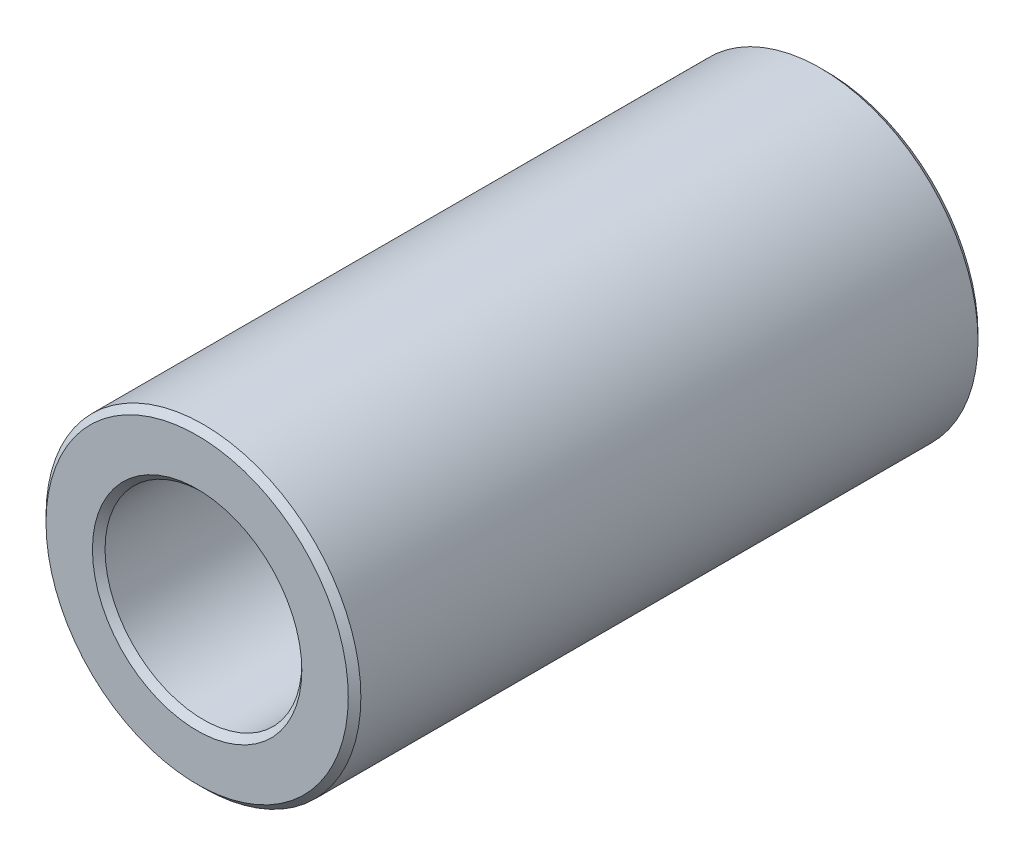
SolidWorks part; units mm, degrees
material "AISI 304"
ref_plane "Front Plane" through (0, 0, 0) normal (0, 0, 1) x (1, 0, 0)
ref_plane "Top Plane" through (0, 0, 0) normal (0, 1, 0) x (1, 0, 0)
ref_plane "Right Plane" through (0, 0, 0) normal (1, 0, 0) x (0, 0, -1)
sketch "Sketch1" plane through (0, 0, 0) normal (1, 0, 0) x (0, 0, -1)
  line L0 (0, 6.35) -> (25.4, 6.35)
  line L1 (25.4, 6.35) -> (25.4, 4.6736)
  line L2 (25.4, 4.6736) -> (15.24, 4.6736)
  line L3 (15.24, 4.6736) -> (15.24, 3.9688)
  line L4 (15.24, 3.9688) -> (0, 3.9687)
  line L5 (0, 3.9687) -> (0, 6.35)
  line L6 (0, 0) -> (42.353, 0) construction
  dimension "D1" = 25.4
  dimension "D2" = 12.7
  dimension "D3" = 9.3472
  dimension "D4" = 7.9375
  dimension "D5" = 10.16
  dimension "D6" = 2.3813
revolve "Revolve1" add sketch "Sketch1" angle 360 about L6
chamfer "Chamfer1" distance 0.254 angle 45 4 edges at (4.6736, 0, -25.4) (3.9687, 0, 0) (6.35, 0, -25.4) (6.35, 0, 0)
chamfer "Chamfer2" distance 0.127 angle 45 1 edges at (3.9688, 0, -15.24)
